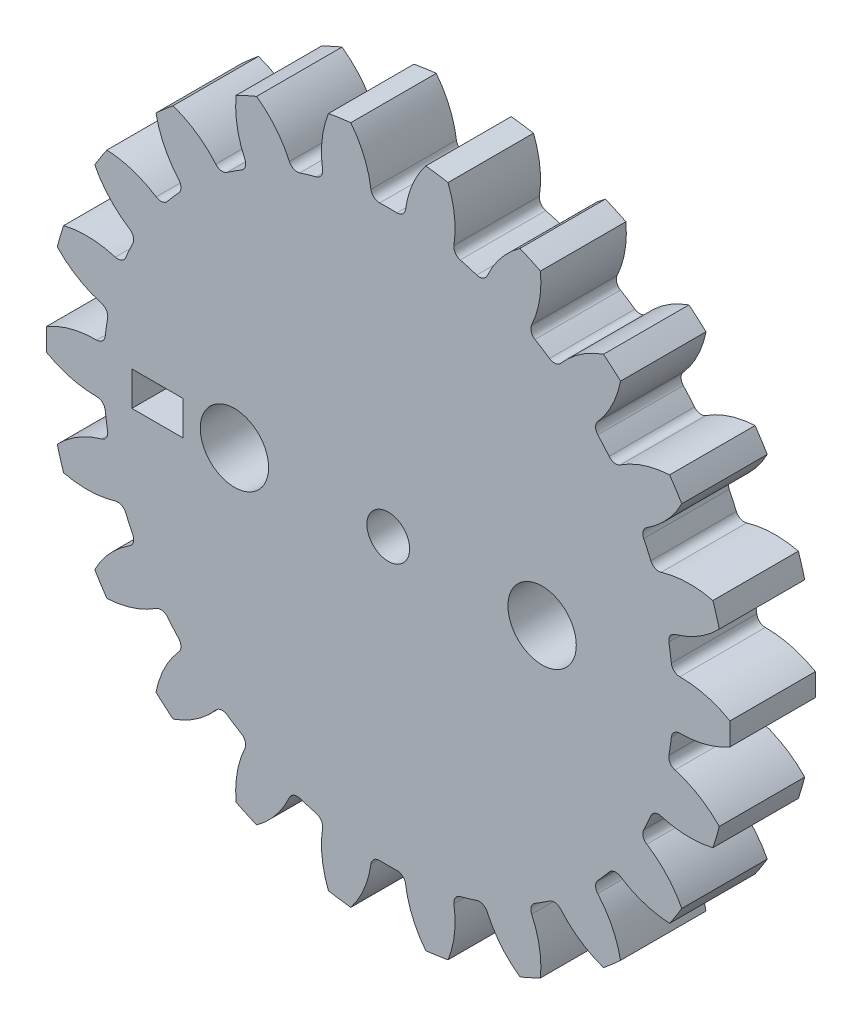
SolidWorks part; units mm, degrees
ref_plane "Front" through (0, 0, 0) normal (0, 0, 1) x (1, 0, 0)
ref_plane "Top" through (0, 0, 0) normal (0, 1, 0) x (1, 0, 0)
ref_plane "Right" through (0, 0, 0) normal (1, 0, 0) x (0, 0, -1)
sketch "Sketch1" plane through (0, 0, 0) normal (0, 0, 1) x (1, 0, 0)
  circle A0 centre (0, 0) radius 16.6667
  circle A1 centre (0, 0) radius 20
  circle A2 centre (0, 0) radius 18.3333
  dimension "D1" = 40
  dimension "D2" = 33.3333
  dimension "D3" = 36.6667
extrude "Boss-Extrude1" add sketch "Sketch1" along normal mid plane 5 contours A1
sketch "Sketch3" plane through (0, 0, 0) normal (0, 0, 1) x (1, 0, 0)
  line L0 (0, 0) -> (0, 20) construction
  line L1 (0, 0) -> (-0.9677, 16.6386) construction
  line L2 (-1.3079, 18.2866) -> (1.3079, 18.2866) construction
  line L3 (-1.8986, 19.9097) -> (0, 14.6932) construction
  line L4 (0, 0) -> (2.8463, 19.7964) construction
  line L5 (1.3079, 18.2866) -> (3.897, 17.9144) construction
  arc A0 (-0.9677, 16.6386) -> (0.9677, 16.6386) centre (0, 0) cw
  arc A4 (2.1919, 19.8795) -> (-2.1919, 19.8795) centre (0, 0) ccw
  circle A5 centre (0, 0) radius 20 construction
  arc A7 (-2.1919, 19.8795) -> (-0.9677, 16.6386) centre (-6.7617, 16.3016) cw
  arc A10 (2.1919, 19.8795) -> (0.9677, 16.6386) centre (6.7617, 16.3016) ccw
  circle A11 centre (0, 0) radius 16.6667 construction
  circle A12 centre (0, 0) radius 18.3333 construction
  dimension "D1" = 20
  dimension "D2" = 8.182
extrude "Cut-Extrude1" cut sketch "Sketch3" against normal through all both and the other way through all
fillet "Fillet2" radius 0.5 2 edges at (0.9677, 16.6386, 0) (-0.9677, 16.6386, 0)
pattern_circular "CirPattern1" count 22 over 360 about axis through (0, 0, 0) along (0, 0, 1) of "Cut-Extrude1", "Fillet2"
sketch "Sketch4" plane through (0, 0, 0) normal (0, 0, 1) x (1, 0, 0)
  circle A0 centre (0, 0) radius 1.25
  dimension "D1" = 2.5
extrude "String_Hole" cut sketch "Sketch4" against normal through all both and the other way through all
sketch "Sketch5" plane through (0, 0, 0) normal (0, 0, 1) x (1, 0, 0)
  line L0 (-9, 0) -> (9, 0) construction
  circle A0 centre (9, 0) radius 2
  circle A1 centre (-9, 0) radius 2
  dimension "D2" = 4
  dimension "D1" = 18
extrude "To_Knuckle_Mount" cut sketch "Sketch5" against normal through all both and the other way through all
sketch "Sketch6" plane through (0, 0, 2.5) normal (0, 0, 1) x (1, 0, 0)
  line L0 (0, 0) -> (-20, 0) construction
  line L2 (-12, -1) -> (-15, -1)
  line L3 (-12, -1) -> (-12, 1)
  line L4 (-12, 1) -> (-15, 1)
  line L5 (-15, -1) -> (-15, 1)
  line L6 (-12, -1) -> (-15, 1) construction
  line L7 (-12, 1) -> (-15, -1) construction
  arc A0 (-19.9891, 0.6595) -> (-19.9891, -0.6595) centre (0, 0) ccw construction
  circle A1 centre (-9, 0) radius 2 construction
  point P6 (-13.5, 0)
  dimension "D1" = 3
  dimension "D2" = 2
  dimension "D3" = 3
extrude "For_Alignment" cut sketch "Sketch6" against normal blind 2
equation "\"od\"= 40'outside diameter"
equation "\"n\"= 22'number of teeth"
equation "\"m\"= \"od\" / ( \"n\" + 2 )'module"
equation "\"p\"= \"m\" * pi'pitch"
equation "\"d\"= \"m\" * \"n\"'primitive diameter"
equation "\"da\"= \"d\" + 2 * \"m\"'head diamater"
equation "\"df\"= \"d\" - 2 * \"m\"'foot diameter"
equation "\"D1@Sketch1\"=\"od\""
equation "\"D2@Sketch1\"=\"df\""
equation "\"D3@Sketch1\"=\"d\""
equation "\"D2@Sketch3\"=180/\"n\""
equation "\"D1@Fillet2\"=.3*\"m\""
equation "\"D1@CirPattern1\"=\"n\""
